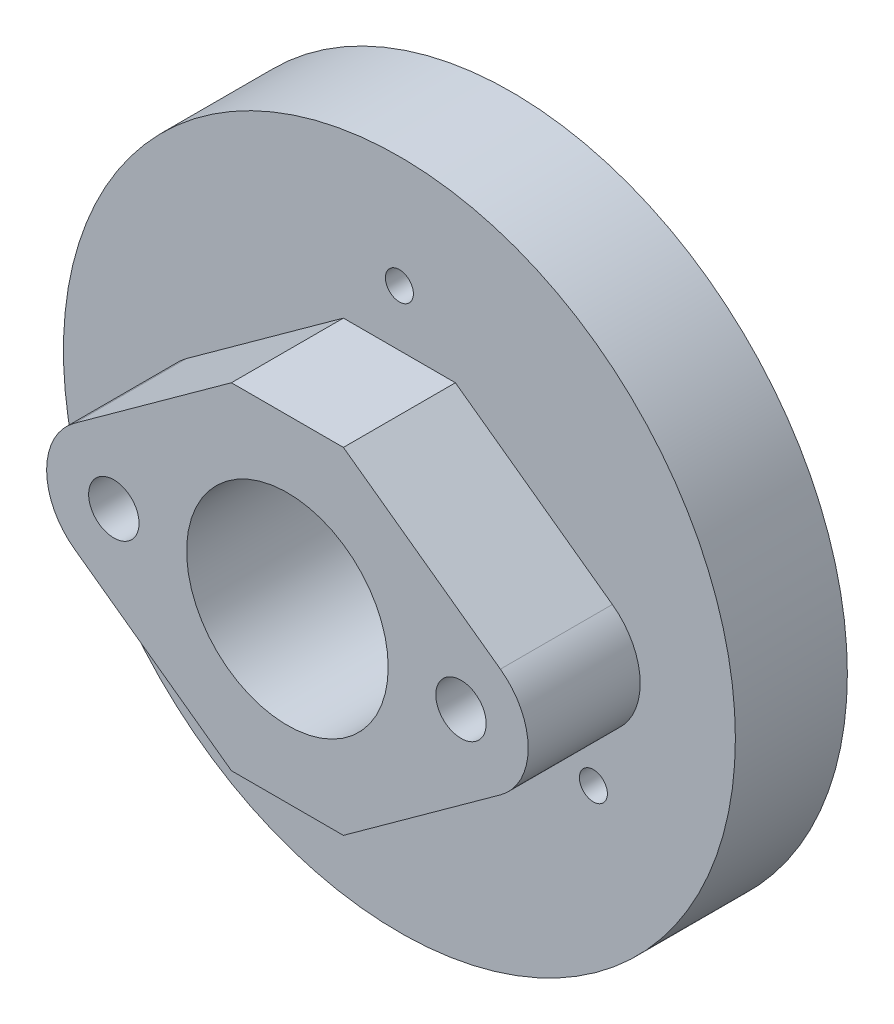
SolidWorks part; units mm, degrees
ref_plane "前视基准面" through (0, 0, 0) normal (0, 0, 1) x (1, 0, 0)
ref_plane "上视基准面" through (0, 0, 0) normal (0, 1, 0) x (1, 0, 0)
ref_plane "右视基准面" through (0, 0, 0) normal (1, 0, 0) x (0, 0, -1)
other "Configuration Table"
sketch "草图1" plane through (0, 0, 0) normal (0, 0, 1) x (1, 0, 0)
  circle A0 centre (0, 0) radius 30
  circle A1 centre (0, 0) radius 9
  circle A2 centre (0, 20) radius 1.25
  circle A3 centre (17.3205, -10) radius 1.25
  circle A4 centre (-17.3205, -10) radius 1.25
  dimension "D1" = 60
  dimension "D2" = 2.5
  dimension "D3" = 18
  dimension "D4" = 20
  dimension "D5" = 3
extrude "凸台-拉伸1" add sketch "草图1" along normal blind 10
sketch "草图2" plane through (0, 0, 10) normal (0, 0, 1) x (1, 0, 0)
  circle A0 centre (-15.5, 0) radius 2.25
  circle A1 centre (15.5, 0) radius 2.25
  point P4 (0, 0)
  point P6 (0, 0)
  dimension "D1" = 4.5
  dimension "D2" = 4.5
  dimension "D3" = 31
  dimension "D4" = 15.5
sketch "草图3" plane through (0, 0, 10) normal (0, 0, 1) x (1, 0, 0)
  line L0 (5, 15) -> (-5, 15)
  line L1 (-5, 15) -> (-19.0165, 4.8615)
  line L3 (-19.0165, -4.8615) -> (-5, -15)
  line L4 (-5, -15) -> (5, -15)
  line L6 (19.0165, -4.8615) -> (5, -15)
  line L7 (5, 15) -> (19.0165, 4.8615)
  arc A0 (-19.0165, 4.8615) -> (-19.0165, -4.8615) centre (-15.5, 0) ccw
  arc A1 (19.0165, 4.8615) -> (19.0165, -4.8615) centre (15.5, 0) cw
  circle A2 centre (15.5, 0) radius 2.25 construction
  circle A3 centre (0, 0) radius 9 construction
  circle A4 centre (0, 0) radius 9
  point P7 (0, 0)
  point P9 (-5.8935, -12.5)
  point P17 (0, 0)
  point P18 (-11.3201, 1.6669)
  point P19 (0, 0)
  point P20 (-18.0143, 3.7287)
  dimension "D3" = 6
  dimension "D7" = 6
  dimension "D1" = 30
  dimension "D2" = 10
  dimension "D4" = 10
  dimension "D5" = 15
  dimension "D6" = 5
extrude "凸台-拉伸2" add sketch "草图3" along normal blind 10
extrude "切除-拉伸1" cut sketch "草图2" against normal through all and the other way through all
sketch "草图4" plane through (0, 0, 0) normal (0, 0, -1) x (-1, 0, 0)
  circle A0 centre (-15.5, 0) radius 4
  circle A1 centre (15.5, 0) radius 4
  dimension "D1" = 8
  dimension "D2" = 8
extrude "切除-拉伸2" cut sketch "草图4" against normal blind 5
